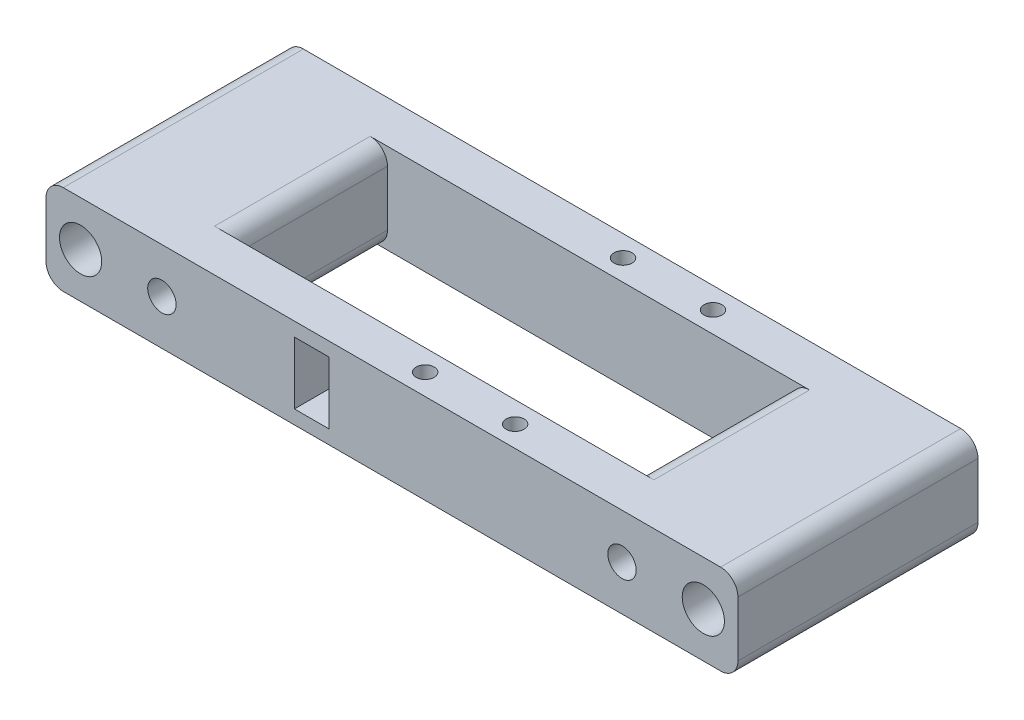
SolidWorks part; units mm, degrees
ref_plane "Front Plane" through (0, 0, 0) normal (0, 0, 1) x (1, 0, 0)
ref_plane "Top Plane" through (0, 0, 0) normal (0, 1, 0) x (1, 0, 0)
ref_plane "Right Plane" through (0, 0, 0) normal (1, 0, 0) x (0, 0, -1)
sketch "Sketch1" plane through (0, 0, 0) normal (0, 0, 1) x (1, 0, 0)
  line L0 (-58.5, 26) -> (-58.5, 0) construction
  line L1 (0, 0) -> (-100, 0)
  line L2 (0, 0) -> (0, 26)
  line L3 (0, 26) -> (-100, 26)
  line L4 (-100, 0) -> (-100, 26)
  circle A0 centre (-90, 13) radius 6.1
  circle A1 centre (-66.5, 13) radius 4.1
  point P9 (-100, 13)
  dimension "D3" = 12.2
  dimension "D4" = 8.2
  dimension "D1" = 100
  dimension "D2" = 26
  dimension "D5" = 23.5
  dimension "D6" = 10
  dimension "D7" = 8
  dimension "D8" = 41.5
extrude "Boss-Extrude1" add sketch "Sketch1" along normal blind 40
sketch "Sketch2" plane through (0, 0, 0) normal (0, 0, -1) x (-1, 0, 0)
  line L1 (100, 26) -> (0, 26)
  line L2 (100, 26) -> (100, 0)
  line L3 (100, 0) -> (0, 0)
  line L4 (0, 26) -> (0, 0)
extrude "Boss-Extrude2" add sketch "Sketch2" along normal blind 29.4
sketch "Sketch3" plane through (0, 26, 0) normal (0, 1, 0) x (1, 0, 0)
  line L0 (0, -40) -> (0, 29.4) construction
  line L1 (0, 17.2) -> (-58.5, 17.2)
  line L2 (0, 17.2) -> (0, -27.8)
  line L3 (0, -27.8) -> (-58.5, -27.8)
  line L4 (-58.5, 17.2) -> (-58.5, -27.8)
  line L5 (-100, -40) -> (-100, 29.4) construction
  line L6 (-100, 29.4) -> (0, 29.4) construction
  line L7 (0, -40) -> (-100, -40) construction
  dimension "D1" = 41.5
  dimension "D2" = 12.2
  dimension "D3" = 12.2
extrude "Cut-Extrude1" cut sketch "Sketch3" against normal up to next
mirror "Mirror2" about plane through (0, 0, 40) normal (-1, 0, 0) of "Boss-Extrude2", "Cut-Extrude1", "Boss-Extrude1"
sketch "Sketch4" plane through (0, 26, 0) normal (0, 1, 0) x (1, 0, 0)
  line L0 (-100, 29.4) -> (100, 29.4) construction
  line L1 (-5.5, 29.4) -> (-5.5, 17.2) construction
  line L2 (58.5, 17.2) -> (-58.5, 17.2) construction
  line L3 (58.5, 17.2) -> (58.5, -27.8) construction
  circle A0 centre (3.5, 23.3) radius 2.6
  circle A1 centre (29.5, 23.3) radius 2.6
  dimension "D1" = 6.1
  dimension "D3" = 9
  dimension "D4" = 26
  dimension "D5" = 5.2
  dimension "D2" = 64
extrude "Cut-Extrude2" cut sketch "Sketch4" against normal through all
sketch "Sketch5" plane through (0, 0, 0) normal (0, -1, 0) x (1, 0, 0)
  line L1 (34.2343, -23.3) -> (31.8671, -19.2)
  line L2 (31.8671, -19.2) -> (27.1329, -19.2)
  line L3 (27.1329, -19.2) -> (24.7657, -23.3)
  line L4 (24.7657, -23.3) -> (27.1329, -27.4)
  line L5 (27.1329, -27.4) -> (31.8671, -27.4)
  line L6 (31.8671, -27.4) -> (34.2343, -23.3)
  line L7 (-1.2343, -23.3) -> (1.1329, -27.4)
  line L8 (1.1329, -27.4) -> (5.8671, -27.4)
  line L9 (5.8671, -27.4) -> (8.2343, -23.3)
  line L10 (8.2343, -23.3) -> (5.8671, -19.2)
  line L11 (5.8671, -19.2) -> (1.1329, -19.2)
  line L12 (1.1329, -19.2) -> (-1.2343, -23.3)
  circle A0 centre (29.5, -23.3) radius 4.1 construction
  circle A1 centre (3.5, -23.3) radius 4.1 construction
  point P1 (0, 0)
  dimension "D1" = 8.2
  dimension "D2" = 8.2
extrude "Cut-Extrude3" cut sketch "Sketch5" against normal blind 4
ref_plane "Plane1" through (0, 0, 5.3) normal (0, 0, 1) x (1, 0, 0)
mirror "Mirror3" about plane through (0, 0, 5.3) normal (0, 0, 1) of "Cut-Extrude3", "Cut-Extrude2"
sketch "Sketch6" plane through (0, 0, 40) normal (0, 0, 1) x (1, 0, 0)
  line L0 (-8.1, 26) -> (-8.1, 0) construction
  line L1 (100, 26) -> (-100, 26) construction
  line L2 (-100, 0) -> (100, 0) construction
  line L3 (0.9, 26) -> (0.9, 4) construction
  line L4 (-100, 26) -> (-100, 0) construction
  line L5 (-18.2, 22) -> (-28.2, 22)
  line L6 (-18.2, 22) -> (-18.2, 4)
  line L7 (-18.2, 4) -> (-28.2, 4)
  line L8 (-28.2, 22) -> (-28.2, 4)
  point P12 (-28.2, 13)
  point P15 (-100, 13)
  dimension "D1" = 9
  dimension "D2" = 10.1
  dimension "D3" = 10
  dimension "D4" = 18
extrude "Cut-Extrude4" cut sketch "Sketch6" against normal up to vertex
fillet "Fillet1" radius 5 8 edges at (58.5, 26, 5.3) (58.5, 0, 5.3) (-58.5, 0, 5.3) (100, 0, 5.3) (100, 26, 5.3) (-100, 0, 5.3) (-100, 26, 5.3) (-58.5, 26, 5.3)
